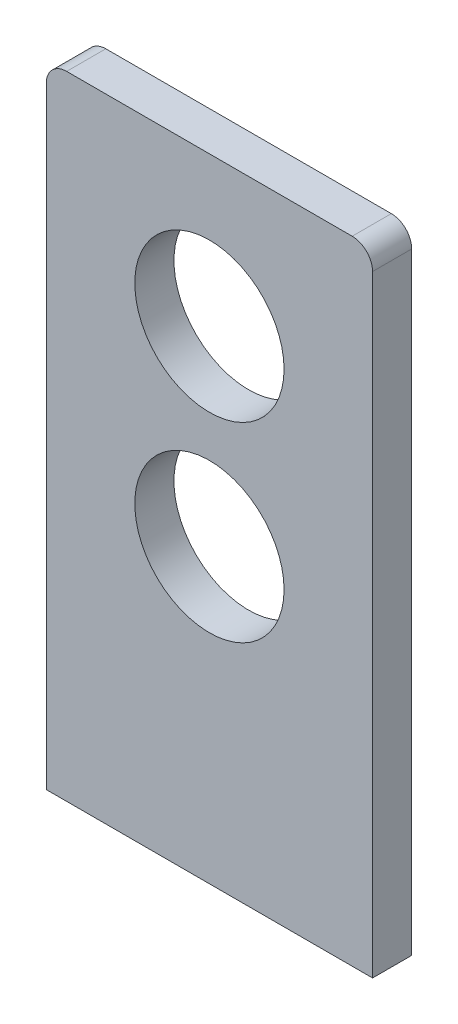
SolidWorks part; units mm, degrees
material "6061-T6 (SS)"
ref_plane "Front Plane" through (0, 0, 0) normal (0, 0, 1) x (1, 0, 0)
ref_plane "Top Plane" through (0, 0, 0) normal (0, 1, 0) x (1, 0, 0)
ref_plane "Right Plane" through (0, 0, 0) normal (1, 0, 0) x (0, 0, -1)
sketch "Sketch1" plane through (0, 0, 0) normal (0, 0, 1) x (1, 0, 0)
  line L1 (-44.45, 76.2) -> (44.45, 76.2)
  line L2 (-50.8, 69.85) -> (-50.8, -69.85)
  line L4 (50.8, 69.85) -> (50.8, -69.85)
  line L5 (-50.8, 76.2) -> (22.8037, -34.2055) construction
  line L8 (-50.8, -69.85) -> (-50.8, -120.65)
  line L9 (-50.8, -120.65) -> (50.8, -120.65)
  line L10 (50.8, -69.85) -> (50.8, -120.65)
  line L11 (-46.5667, -69.85) -> (50.8, 76.2) construction
  circle A0 centre (0, 29.718) radius 23.241
  circle A1 centre (0, -29.718) radius 23.241
  arc A4 (50.8, 69.85) -> (44.45, 76.2) centre (44.45, 69.85) ccw
  arc A5 (-50.8, 69.85) -> (-44.45, 76.2) centre (-44.45, 69.85) cw
  point P0 (0, 0)
  dimension "D3" = 50.8
extrude "Boss-Extrude1" add sketch "Sketch1" against normal blind 12.192
equation "\"F\"= 600'Applied force"
equation "\"Yst\"= 39885.32'Yield strength"
equation "\"Sf\"= 4'Safety factor"
equation "\"def\"= .005'Deflection"
equation "\"Lst\"= 5'Length of strap"
equation "\"E\"= 10007604'Modulus of elasticity"
equation "\"Dst\"= ( ( \"F\" * \"Lst\" * \"Sf\" * 32 * 2 ) / ( \"Yst\" * 3.14159 ) ) ^ ( 1 / 3 )'Driven diameter of feauture A"
equation "\"Lftb\"= 4'Chosen length of feature B"
equation "\"hftb\"= ( ( \"F\" * \"Lftb\" * \"Sf\" * 6 * 2 ) / ( \"Dst\" * \"Yst\" ) ) ^ ( 1 / 2 )'Driven height of feature B"
equation "\"Bftc\"= 2.5'Base of feature C, from T-beam dim"
equation "\"hftc\"= ( ( \"F\" * \"Lst\" * \"Sf\" * 2 * 6 ) / ( \"Bftc\" * \"Yst\" ) ) ^ ( 1 / 2 )'Driven height of feature C"
equation "\"hftd\"= 1.5'Chosen height of feature D"
equation "\"cftd\"= \"hftd\" / 2'Neutral axis of feature D (distance)"
equation "\"bftd\"= ( \"F\" * \"Lst\" * \"cftd\" * \"Sf\" * 2 * 12 ) / ( \"Yst\" * ( \"hftd\" ^ 3 ) )'Driven base of feature D"
equation "\"bfte\"= 1'Base of feature E, from T-beam dim"
equation "\"hfte\"= ( ( \"F\" * \"Lst\" * \"Sf\" * 6 * 2 ) / ( \"Yst\" * \"bfte\" ) ) ^ ( 1 / 2 )'Driven height of feature E"
equation "\"hlink\"= 6'Chosen height of link"
equation "\"blink\"= 2.25'Chosen base of link"
equation "\"clink\"= 3'Neutral axis of link (distance)"
equation "\"tlink\"= ( \"F\" * \"hlink\" * \"clink\" * \"Sf\" * 12 * 2 ) / ( \"Yst\" * ( \"hlink\" ^ 3 ) )'Driven thickness of link"
